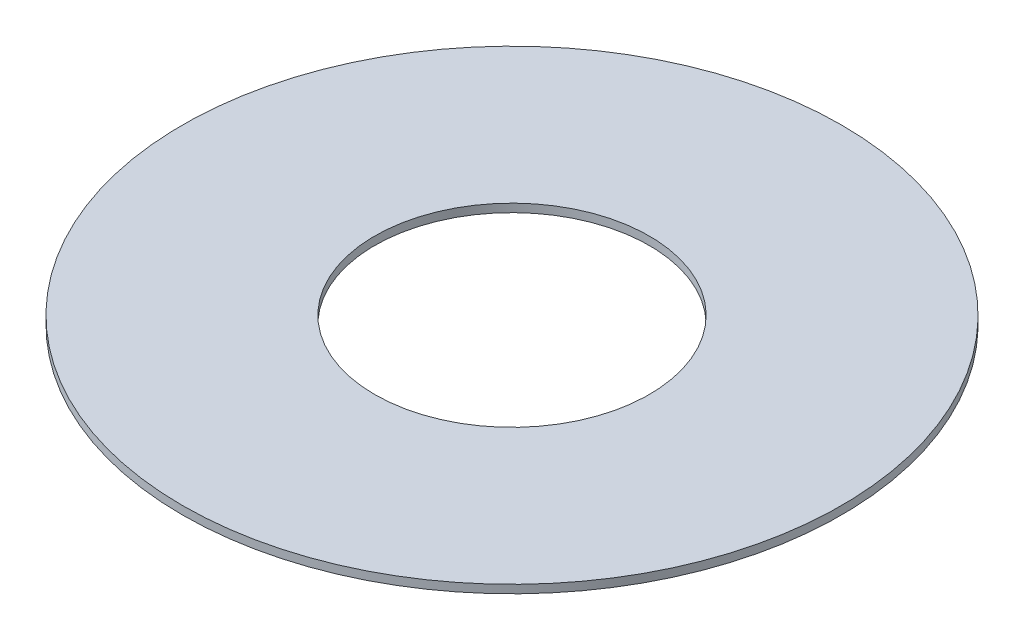
SolidWorks part; units mm, degrees
ref_plane "Front Plane" through (0, 0, 0) normal (0, 0, 1) x (1, 0, 0)
ref_plane "Top Plane" through (0, 0, 0) normal (0, 1, 0) x (1, 0, 0)
ref_plane "Right Plane" through (0, 0, 0) normal (1, 0, 0) x (0, 0, -1)
sketch "Sketch1" plane through (0, 0, 0) normal (0, 1, 0) x (1, 0, 0)
  circle A0 centre (0, 0) radius 120
  circle A1 centre (0, 0) radius 50
  dimension "D1" = 240
  dimension "D2" = 100
extrude "Boss-Extrude1" add sketch "Sketch1" along normal mid plane 3
